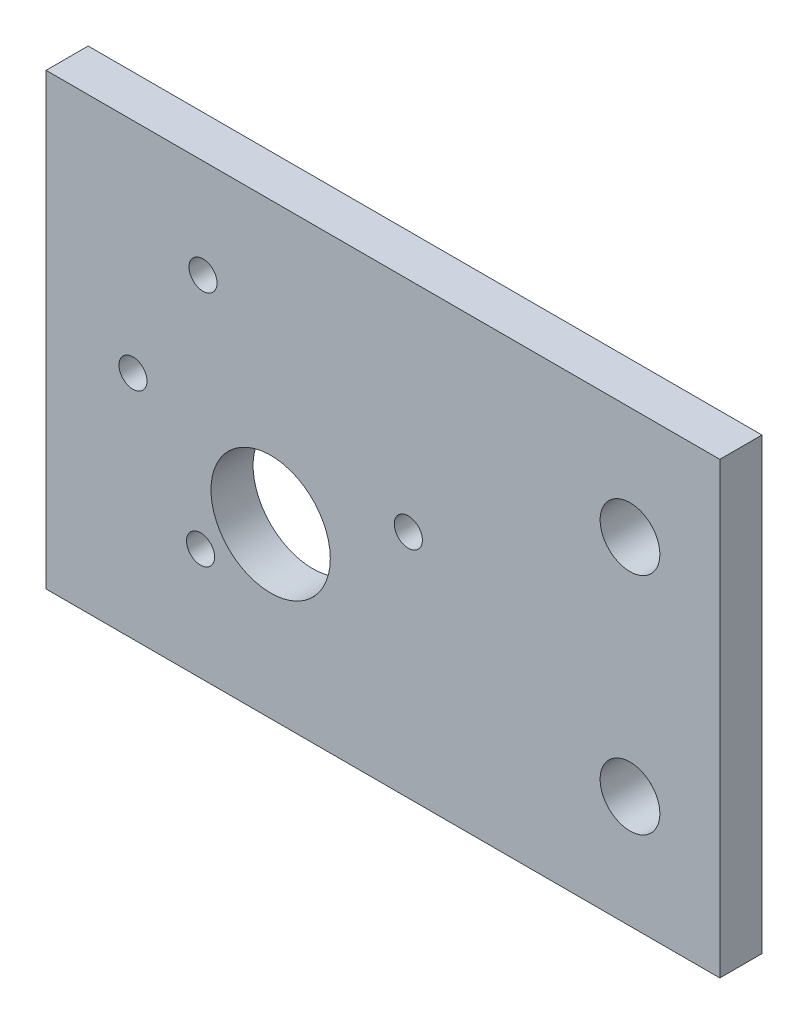
SolidWorks part; units mm, degrees
material "1060 Alloy"
ref_plane "Front" through (0, 0, 0) normal (0, 0, 1) x (1, 0, 0)
ref_plane "Top" through (0, 0, 0) normal (0, 1, 0) x (1, 0, 0)
ref_plane "Right" through (0, 0, 0) normal (1, 0, 0) x (0, 0, -1)
sketch "Sketch1" plane through (0, 0, 0) normal (0, 0, 1) x (1, 0, 0)
  line L1 (-38.1, 25.4) -> (38.1, 25.4)
  line L2 (-38.1, 25.4) -> (-38.1, -25.4)
  line L3 (-38.1, -25.4) -> (38.1, -25.4)
  line L4 (38.1, 25.4) -> (38.1, -25.4)
  line L5 (-38.1, 25.4) -> (38.1, -25.4) construction
  line L6 (-38.1, -25.4) -> (38.1, 25.4) construction
  point P0 (0, 0)
  dimension "D1" = 76.2
  dimension "D2" = 50.8
extrude "Boss-Extrude1" add sketch "Sketch1" along normal blind 4.7625
hole_wizard "17/32 (0.53125) Diameter Hole1" positions "Sketch3" profile "Sketch4" hole size "17/32" standard "ANSI Inch" end condition through all
sketch "Sketch3" plane through (0, 0, 4.7625) normal (0, 0, 1) x (1, 0, 0)
  line L0 (-38.1, 25.4) -> (-38.1, -25.4) construction
  line L1 (38.1, 25.4) -> (-38.1, 25.4) construction
  point P0 (-12.7, -6.35)
  dimension "D1" = 25.4
  dimension "D2" = 31.75
sketch "Sketch4" plane through (-12.7, -6.35, 4.7625) normal (1, 0, 0) x (0, -1, 0)
  line L0 (0, 0) -> (0, 4.7625)
  line L1 (0, 4.7625) -> (6.7469, 4.7625)
  line L2 (6.7469, 4.7625) -> (6.7469, 0)
  line L5 (6.7469, 0) -> (0, 0)
  line L11 (0, -6.35) -> (0, 107.95) construction
  dimension "Thru Hole Dia." = 13.4937
  dimension "Thru Hole Depth" = 4.7625
sketch "Sketch5" plane through (0, 0, 4.7625) normal (0, 0, 1) x (1, 0, 0)
  circle A0 centre (-12.7, 0.6604) radius 15.5702 construction
  circle A1 centre (-12.7, -6.35) radius 6.7469 construction
  circle A2 centre (-12.7, -6.35) radius 6.7469 construction
  dimension "D1" = 31.1404
  dimension "D2" = 7.0104
hole_wizard "1/8 (0.125) Diameter Hole1" positions "Sketch6" profile "Sketch7" hole size "1/8" standard "ANSI Inch" end condition through all
sketch "Sketch6" plane through (0, 0, 4.7625) normal (0, 0, 1) x (1, 0, 0)
  circle A0 centre (-12.7, 0.6604) radius 15.5702 construction
  point P0 (-20.3454, 14.2243)
  point P2 (-28.2702, 0.6604)
  point P4 (-20.6248, -12.7422)
  point P6 (2.8702, 0.6604)
  dimension "D1" = 7.6454
  dimension "D2" = 7.9248
sketch "Sketch7" plane through (-20.3454, 14.2243, 4.7625) normal (1, 0, 0) x (0, -1, 0)
  line L0 (0, 0) -> (0, 4.7625)
  line L1 (0, 4.7625) -> (1.5875, 4.7625)
  line L2 (1.5875, 4.7625) -> (1.5875, 0)
  line L5 (1.5875, 0) -> (0, 0)
  line L11 (0, -6.35) -> (0, 107.95) construction
  dimension "Thru Hole Dia." = 3.175
  dimension "Thru Hole Depth" = 4.7625
hole_wizard "H (0.266) Diameter Hole1" positions "Sketch8" profile "Sketch9" hole size "H" standard "ANSI Inch" end condition through all
sketch "Sketch8" plane through (0, 0, 4.7625) normal (0, 0, 1) x (1, 0, 0)
  line L0 (38.1, -25.4) -> (38.1, 25.4) construction
  line L1 (38.1, 25.4) -> (-38.1, 25.4) construction
  point P0 (27.94, 12.7)
  point P2 (27.94, -12.7)
  dimension "D1" = 10.16
  dimension "D2" = 12.7
  dimension "D3" = 38.1
sketch "Sketch9" plane through (27.94, 12.7, 4.7625) normal (1, 0, 0) x (0, -1, 0)
  line L0 (0, 0) -> (0, 4.7625)
  line L1 (0, 4.7625) -> (3.3782, 4.7625)
  line L2 (3.3782, 4.7625) -> (3.3782, 0)
  line L5 (3.3782, 0) -> (0, 0)
  line L11 (0, -6.35) -> (0, 107.95) construction
  dimension "Thru Hole Dia." = 6.7564
  dimension "Thru Hole Depth" = 4.7625
